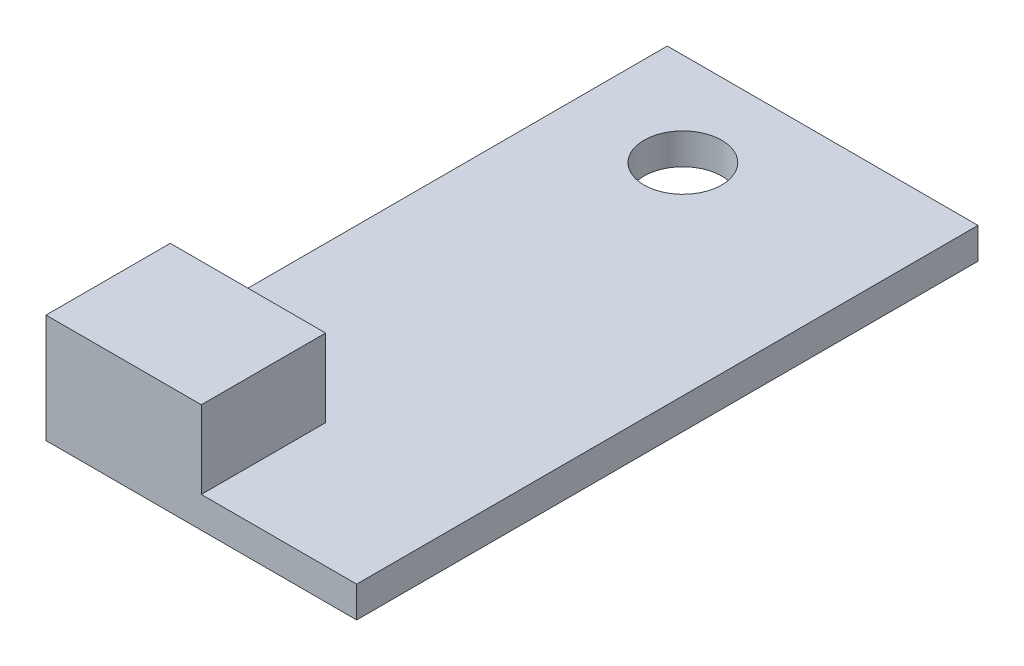
SolidWorks part; units mm, degrees
ref_plane "Alzado" through (0, 0, 0) normal (0, 0, 1) x (1, 0, 0)
ref_plane "Planta" through (0, 0, 0) normal (0, 1, 0) x (1, 0, 0)
ref_plane "Vista lateral" through (0, 0, 0) normal (1, 0, 0) x (0, 0, -1)
sketch "Croquis1" plane through (0, 0, 0) normal (0, 1, 0) x (1, 0, 0)
  line L1 (-50, -100) -> (50, -100)
  line L2 (-50, -100) -> (-50, 100)
  line L3 (-50, 100) -> (50, 100)
  line L4 (50, -100) -> (50, 100)
  line L5 (-50, -100) -> (50, 100) construction
  line L6 (-50, 100) -> (50, -100) construction
  point P0 (0, 0)
  dimension "D1" = 200
  dimension "D2" = 100
extrude "Saliente-Extruir1" add sketch "Croquis1" along normal blind 10 contours L2 L1 L4 L3
sketch "Croquis2" plane through (0, 10, 0) normal (0, 1, 0) x (1, 0, 0)
  line L1 (-50, -100) -> (0, -100)
  line L2 (-50, -100) -> (-50, -60)
  line L3 (-50, -60) -> (0, -60)
  line L4 (0, -100) -> (0, -60)
  dimension "D1" = 50
  dimension "D2" = 40
extrude "Saliente-Extruir2" add sketch "Croquis2" along normal blind 25 contours L2 L1 L4 L3
hole_wizard "Diámetro de taladro Ø25.0 (25)2" positions "Croquis5" profile "Croquis6" hole size "Ø25.0" standard "Ansi Metric" end condition through all
sketch "Croquis5" plane through (0, 10, 0) normal (0, 1, 0) x (1, 0, 0)
  line L0 (-50, 100) -> (50, 100) construction
  line L1 (-50, -60) -> (-50, 100) construction
  point P0 (-15, 70)
  dimension "D1" = 30
  dimension "D2" = 35
sketch "Croquis6" plane through (-15, 10, -70) normal (1, 0, 0) x (0, 0, 1)
  line L0 (0, 0) -> (0, 10)
  line L1 (0, 10) -> (12.5, 10)
  line L2 (12.5, 10) -> (12.5, 0)
  line L5 (12.5, 0) -> (0, 0)
  line L11 (0, -6.35) -> (0, 107.95) construction
  dimension "Diámetro de taladro hasta el siguiente" = 25
  dimension "Profundidad de taladro hasta el siguiente" = 10
